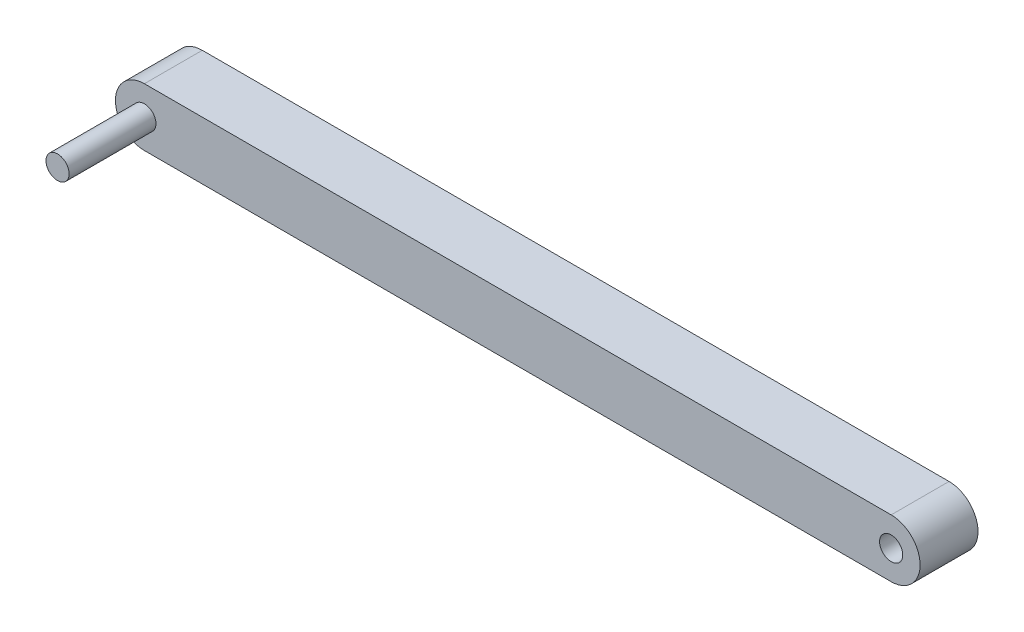
SolidWorks part; units mm, degrees
ref_plane "Front Plane" through (0, 0, 0) normal (0, 0, 1) x (1, 0, 0)
ref_plane "Top Plane" through (0, 0, 0) normal (0, 1, 0) x (1, 0, 0)
ref_plane "Right Plane" through (0, 0, 0) normal (1, 0, 0) x (0, 0, -1)
sketch "Sketch1" plane through (0, 0, 0) normal (0, 0, 1) x (1, 0, 0)
  line L0 (0, 0) -> (1290, 0)
  line L1 (1290, 0) -> (1290, 50)
  line L2 (1290, 100) -> (0, 100)
  line L3 (0, 0) -> (0, 50)
  arc A0 (1290, 0) -> (1290, 100) centre (1290, 50) ccw
  arc A1 (0, 0) -> (0, 100) centre (0, 50) cw
extrude "Boss-Extrude1" add sketch "Sketch1" along normal blind 100
sketch "Sketch2" plane through (0, 0, 100) normal (0, 0, 1) x (1, 0, 0)
  line L0 (0, 0) -> (0, 50)
  circle A0 centre (0, 50) radius 20
sketch "Sketch3" plane through (0, 0, 100) normal (0, 0, 1) x (1, 0, 0)
  line L0 (1290, 0) -> (1290, 50)
  circle A0 centre (1290, 50) radius 20
extrude "Cut-Extrude1" cut sketch "Sketch3" against normal blind 100
extrude "Boss-Extrude3" add sketch "Sketch2" along normal blind 150 contours A0
